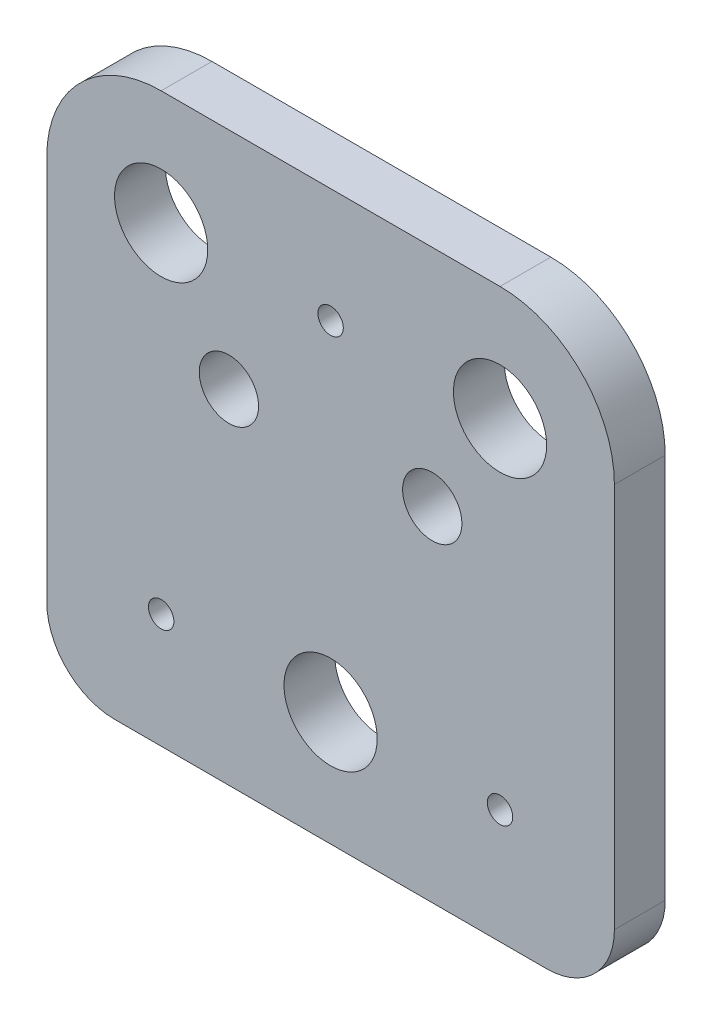
SolidWorks part; units mm, degrees
ref_plane "Plano frontal" through (0, 0, 0) normal (0, 0, 1) x (1, 0, 0)
ref_plane "Plano superior" through (0, 0, 0) normal (0, 1, 0) x (1, 0, 0)
ref_plane "Plano direito" through (0, 0, 0) normal (1, 0, 0) x (0, 0, -1)
sketch "Esboço1" plane through (0, 0, 0) normal (0, 0, 1) x (1, 0, 0)
  line L0 (-20, 33.5) -> (20, 33.5)
  line L1 (-20, 20) -> (20, 20) construction
  line L2 (-20, 20) -> (-20, -20) construction
  line L3 (-20, -20) -> (20, -20) construction
  line L4 (20, 20) -> (20, -20) construction
  line L5 (-20, 20) -> (20, -20) construction
  line L6 (-20, -20) -> (20, 20) construction
  line L9 (33.5, -20) -> (33.5, 20)
  line L10 (20, -33.5) -> (-20, -33.5)
  line L11 (-33.5, -20) -> (-33.5, 20)
  circle A0 centre (-20, 20) radius 5.5
  circle A1 centre (20, 20) radius 5.5
  circle A2 centre (0, -20) radius 5.5
  arc A3 (-20, 33.5) -> (-33.5, 20) centre (-20, 20) ccw
  arc A4 (33.5, 20) -> (20, 33.5) centre (20, 20) ccw
  arc A6 (20, -33.5) -> (33.5, -20) centre (20, -20) ccw
  arc A7 (-33.5, -20) -> (-20, -33.5) centre (-20, -20) ccw
  point P0 (0, 0)
  point P13 (-8, 22)
  point P14 (0, -20)
  point P15 (32, 22)
  point P18 (12, -22)
  dimension "D3" = 11
  dimension "D4" = 13.5
  dimension "D1" = 40
  dimension "D2" = 40
extrude "Ressalto-extrusão1" add sketch "Esboço1" along normal blind 6
sketch "Esboço2" plane through (0, 0, 0) normal (0, 0, -1) x (-1, 0, 0)
  line L1 (-33.5, -20) -> (-20, -20)
  line L2 (-33.5, -20) -> (-33.5, -33.5)
  line L3 (-33.5, -33.5) -> (-20, -33.5)
  line L4 (-20, -20) -> (-20, -33.5)
  line L5 (33.5, -20) -> (20, -20)
  line L6 (33.5, -20) -> (33.5, -33.5)
  line L7 (33.5, -33.5) -> (20, -33.5)
  line L8 (20, -20) -> (20, -33.5)
  arc A0 (20, -33.5) -> (33.5, -20) centre (20, -20) ccw construction
extrude "Ressalto-extrusão2" add sketch "Esboço2" against normal up to surface (6 mm away) up to face at (25.5, 20, 6)
fillet "Filete1" radius 8 2 edges at (33.5, -33.5, 3) (-33.5, -33.5, 3)
ref_plane "Plano1" through (0, 0, 0) normal (-1, 0, 0) x (0, 0, 1)
sketch "Esboço3" plane through (0, 0, 0) normal (0, 0, -1) x (-1, 0, 0)
  line L1 (-20, 20) -> (20, 20) construction
  line L2 (-20, 20) -> (-20, -20) construction
  line L3 (-20, -20) -> (20, -20) construction
  line L4 (20, 20) -> (20, -20) construction
  circle A5 centre (0, 20) radius 1.5
  circle A6 centre (20, -20) radius 1.5
  circle A7 centre (-20, -20) radius 1.5
  dimension "D2" = 3
  dimension "D1" = 40
extrude "Corte-extrusão1" cut sketch "Esboço3" against normal up to surface (6 mm away) up to face at (0, -1.0902, 6)
sketch "Esboço5" plane through (0, 0, 6) normal (0, 0, 1) x (1, 0, 0)
  circle A0 centre (12, 7) radius 1.65 construction
  circle A1 centre (-12, 7) radius 1.65 construction
  circle A2 centre (12, 7) radius 1.65 construction
  circle A3 centre (-12, 7) radius 1.65 construction
  circle A4 centre (-12, 7) radius 3.5
  circle A5 centre (12, 7) radius 3.5
  dimension "D1" = 7
extrude "Corte-extrusão2" cut sketch "Esboço5" against normal up to surface (6 mm away) up to face at (-21.5, -20, 0)
